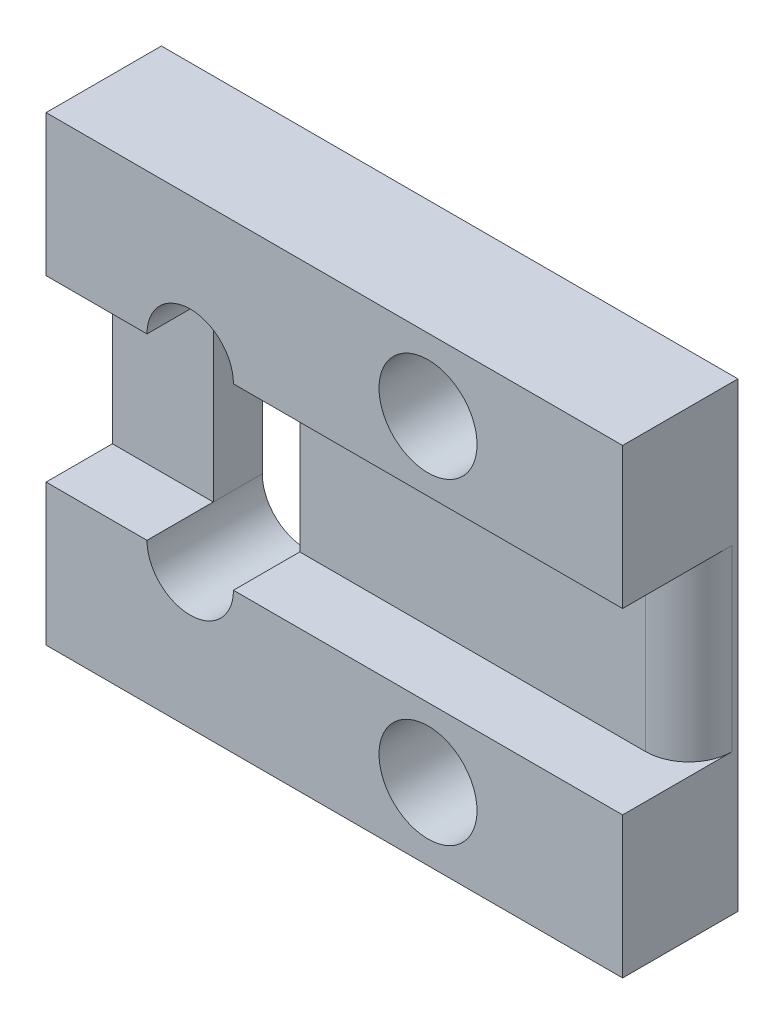
SolidWorks part; units mm, degrees
ref_plane "Front Plane" through (0, 0, 0) normal (0, 0, 1) x (1, 0, 0)
ref_plane "Top Plane" through (0, 0, 0) normal (0, 1, 0) x (1, 0, 0)
ref_plane "Right Plane" through (0, 0, 0) normal (1, 0, 0) x (0, 0, -1)
sketch "Sketch1" plane through (0, 0, 0) normal (0, 0, 1) x (1, 0, 0)
  line L0 (5, 11.1) -> (5, 4.9) construction
  line L1 (0, 0) -> (20, 0)
  line L2 (0, 0) -> (0, 16)
  line L3 (0, 16) -> (20, 16)
  line L4 (20, 0) -> (20, 16)
  line L5 (6.5, 11.1) -> (6.5, 4.9)
  line L6 (3.5, 11.1) -> (3.5, 4.9)
  line L10 (42.427, 8) -> (-3.8546, 8) construction
  arc A0 (6.5, 11.1) -> (3.5, 11.1) centre (5, 11.1) ccw
  arc A1 (3.5, 4.9) -> (6.5, 4.9) centre (5, 4.9) ccw
  point P7 (5, 8)
  point P28 (20, 8)
  dimension "D1" = 16
  dimension "D2" = 20
  dimension "D3" = 6.2
  dimension "D5" = 3
extrude "Boss-Extrude1" add sketch "Sketch1" along normal blind 4
hole_wizard "M3 Clearance Hole1" positions "Sketch3" profile "Sketch2" hole size "M3" standard "ISO" end condition through all
sketch "Sketch3" plane through (0, 0, 4) normal (0, 0, 1) x (1, 0, 0)
  line L0 (20, 8) -> (6.5, 8) construction
  line L2 (20, 0) -> (20, 16) construction
  line L4 (6.5, 4.9) -> (6.5, 11.1) construction
  point P0 (13.25, 13.5)
  point P12 (20, 8)
  point P16 (13.25, 2.5)
  point P29 (13.25, 8)
  dimension "D2" = 11
sketch "Sketch2" plane through (13.25, 13.5, 4) normal (1, 0, 0) x (0, -1, 0)
  line L0 (0, 0) -> (0, 4)
  line L1 (0, 4) -> (1.7, 4)
  line L2 (1.7, 4) -> (1.7, 0)
  line L5 (1.7, 0) -> (0, 0)
  line L11 (0, -6.35) -> (0, 107.95) construction
  dimension "Thru Hole Dia." = 3.4
  dimension "Thru Hole Depth" = 4
sketch "Sketch4" plane through (0, 0, 4) normal (0, 0, 1) x (1, 0, 0)
  line L0 (20, 8) -> (0, 8) construction
  line L1 (-1.2736, 11.1) -> (26.4128, 11.1)
  line L2 (-1.2736, 11.1) -> (-1.2736, 4.9)
  line L3 (-1.2736, 4.9) -> (26.4128, 4.9)
  line L4 (26.4128, 11.1) -> (26.4128, 4.9)
  line L5 (20, 0) -> (20, 16) construction
  line L6 (0, 16) -> (0, 0) construction
  dimension "D1" = 6.2
extrude "Cut-Extrude1" cut sketch "Sketch4" against normal blind 2.3
fillet "Fillet1" radius 1.5 1 edges at (20, 8, 1.7)
